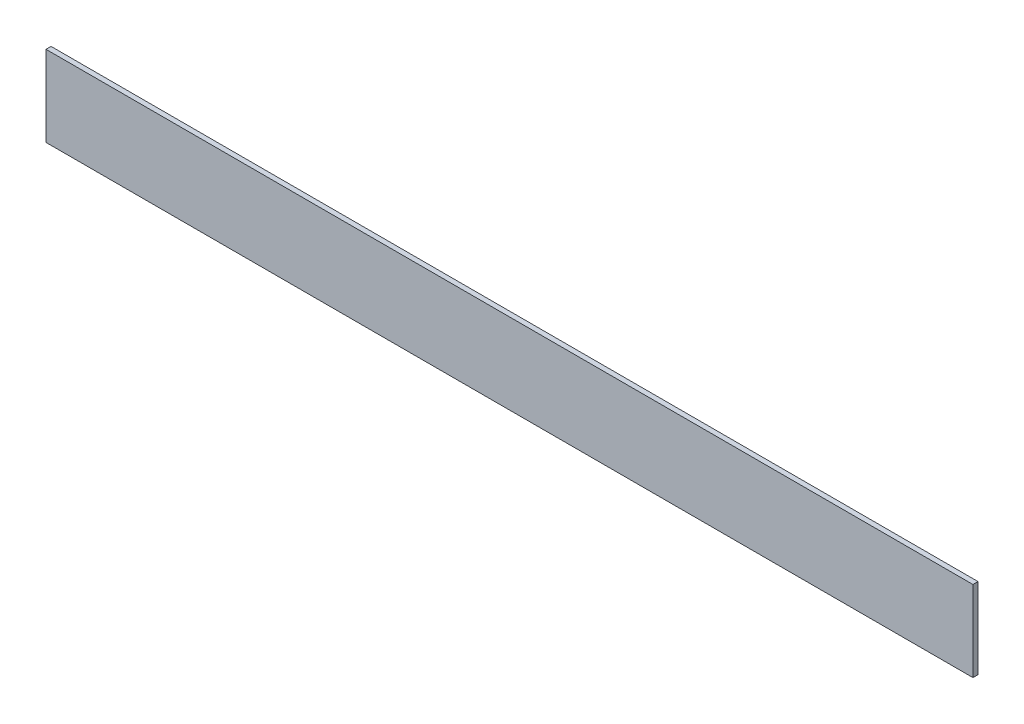
SolidWorks part; units mm, degrees
ref_plane "前视基准面" through (0, 0, 0) normal (0, 0, 1) x (1, 0, 0)
ref_plane "上视基准面" through (0, 0, 0) normal (0, 1, 0) x (1, 0, 0)
ref_plane "右视基准面" through (0, 0, 0) normal (1, 0, 0) x (0, 0, -1)
ref_plane "基准面4" through (0, 0, -20) normal (0, 0, 1) x (1, 0, 0)
sketch "草图2" plane through (0, 0, -20) normal (0, 0, 1) x (1, 0, 0)
  line L1 (-981.5936, -1380) -> (468.4064, -1380) construction
  line L2 (-981.5936, -1465) -> (-981.5936, 0) construction
  line L5 (-989.0936, -1260) -> (475.9064, -1260)
  line L6 (475.9064, -1387.5) -> (475.9064, -1260)
  line L7 (-989.0936, -1387.5) -> (475.9064, -1387.5)
  line L8 (-989.0936, -1387.5) -> (-989.0936, -1260)
  dimension "D1" = 120
  dimension "D2" = 127.5
  dimension "D3" = 7.5
extrude "凸台-拉伸1" add sketch "草图2" along normal mid plane 8
